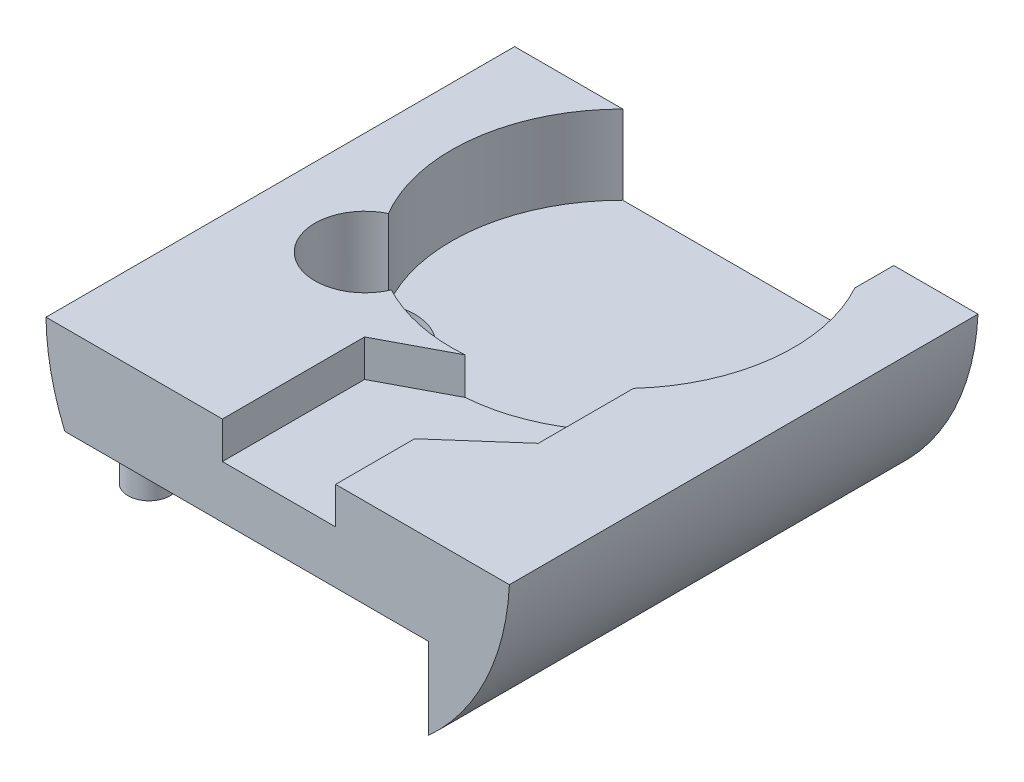
SolidWorks part; units mm, degrees
ref_plane "Front Plane" through (0, 0, 0) normal (0, 0, 1) x (1, 0, 0)
ref_plane "Top Plane" through (0, 0, 0) normal (0, 1, 0) x (1, 0, 0)
ref_plane "Right Plane" through (0, 0, 0) normal (1, 0, 0) x (0, 0, -1)
sketch "Sketch1" plane through (0, 0, 0) normal (0, 1, 0) x (1, 0, 0)
  line L0 (-43.9761, 42) -> (-43.9761, -42)
  line L1 (-43.9761, -42) -> (43.9761, -42)
  line L2 (43.9761, 42) -> (43.9761, -42)
  line L3 (-43.9761, 42) -> (43.9761, 42)
sketch "Sketch2" plane through (0, 0, 0) normal (0, 1, 0) x (1, 0, 0)
extrude "Boss-Extrude1" add sketch "Sketch1" along normal blind 44
sketch "Sketch3" plane through (0, 0, 42) normal (0, 0, 1) x (1, 0, 0)
  line L1 (-43.9761, 44) -> (43.9761, 44) construction
  line L2 (-43.9761, 0) -> (43.9761, 0) construction
  line L3 (-21, 0) -> (21, 0)
  line L5 (-43.9761, 44) -> (-43.9761, -11.9712)
  line L6 (-43.9761, -11.9712) -> (43.9761, -11.9712)
  line L7 (43.9761, -11.9712) -> (43.9761, 44)
  arc A0 (-43.9761, 44) -> (-21, 0) centre (29.2513, 54.2392) ccw
  arc A1 (21, 0) -> (43.9761, 44) centre (-19.1343, 48.9563) ccw
  point P9 (0, 0)
  dimension "D1" = 42
extrude "Cut-Extrude1" cut sketch "Sketch3" against normal through all
sketch "Sketch4" plane through (0, 0, 42) normal (0, 0, 1) x (1, 0, 0)
  line L2 (-40.0146, 44.5539) -> (-43.9761, 44)
  line L3 (-19.4066, 4) -> (19.5435, 4)
  line L4 (-19.4066, 4) -> (19.5435, 4)
  line L5 (-21, 0) -> (21, 0)
  line L6 (-21, 0) -> (21, 0) construction
  line L7 (39.9883, 44.3132) -> (43.9761, 44)
  arc A4 (-43.9761, 44) -> (-21, 0) centre (29.2513, 54.2392) ccw
  arc A5 (43.9761, 44) -> (21, 0) centre (-19.1343, 48.9563) cw
  arc A6 (19.5435, 4) -> (39.9883, 44.3132) centre (-19.1343, 48.9563) ccw
  arc A7 (-40.0146, 44.5539) -> (-19.4066, 4) centre (29.2513, 54.2392) ccw
  arc A8 (19.5435, 4) -> (39.9883, 44.3132) centre (-19.1343, 48.9563) ccw
  arc A9 (-40.0146, 44.5539) -> (-19.4066, 4) centre (29.2513, 54.2392) ccw
  dimension "D1" = 4
extrude "Cut-Extrude2" cut sketch "Sketch4" against normal blind 94
sketch "Sketch6" plane through (0, 0, -42) normal (0, 0, -1) x (-1, 0, 0)
  line L4 (-19.5435, 4) -> (19.4066, 4)
  line L5 (39.9349, 44) -> (-39.9629, 44)
  line L6 (-19.5435, 4) -> (19.4066, 4)
  line L7 (39.9349, 44) -> (-39.9629, 44)
  arc A4 (19.4066, 4) -> (39.9349, 44) centre (-29.2513, 54.2392) ccw
  arc A5 (-39.9629, 44) -> (-19.5435, 4) centre (19.1343, 48.9563) ccw
  arc A6 (19.4066, 4) -> (39.9349, 44) centre (-29.2513, 54.2392) ccw
  arc A7 (-39.9629, 44) -> (-19.5435, 4) centre (19.1343, 48.9563) ccw
  dimension "D1" = 0
extrude "Boss-Extrude2" add sketch "Sketch6" along normal blind 5
sketch "Sketch8" plane through (0, 0, -47) normal (0, 0, -1) x (-1, 0, 0)
  line L26 (-19.5435, 4) -> (19.4066, 4)
  line L27 (-21.7534, 6) -> (21.39, 6)
  arc A0 (-39.9629, 44) -> (-19.5435, 4) centre (19.1343, 48.9563) ccw construction
  arc A1 (19.4066, 4) -> (39.9349, 44) centre (-29.2513, 54.2392) ccw construction
  arc A2 (-21.7534, 6) -> (-19.5435, 4) centre (19.1343, 48.9563) ccw
  arc A3 (21.39, 6) -> (19.4066, 4) centre (-29.2513, 54.2392) cw
  dimension "D1" = 2
sketch "Sketch10" plane through (0, 0, -47) normal (0, 0, -1) x (-1, 0, 0)
extrude "Cut-Extrude4" cut sketch "Sketch8" against normal through all
sketch "Sketch11" plane through (0, 0, -47) normal (0, 0, -1) x (-1, 0, 0)
  line L0 (-21.7534, 6) -> (21.39, 6)
  line L1 (-44.6152, 44) -> (43.3848, 44)
  arc A2 (21.39, 6) -> (43.3848, 44) centre (-1.3442, 44.5242) ccw
  arc A3 (-21.7534, 6) -> (-44.6152, 44) centre (2.13, 46.246) cw
  point P7 (-0.6152, 44)
  dimension "D1" = 88
extrude "Boss-Extrude3" add sketch "Sketch11" against normal up to surface (89 mm away) up to face at (0.2349, 24.2233, 42)
sketch "Sketch12" plane through (0, 6, 0) normal (0, -1, 0) x (1, 0, 0)
  line L0 (-21.39, 42) -> (21.7534, 42) construction
  line L1 (29.2534, 42) -> (-37.39, 42)
  line L2 (29.2534, 42) -> (29.2534, -47)
  line L3 (29.2534, -47) -> (-37.39, -47)
  line L4 (-37.39, 42) -> (-37.39, -47)
  line L5 (-21.39, -47) -> (21.7534, -47) construction
  line L6 (21.7534, 42) -> (21.7534, -47) construction
  line L7 (-21.39, 42) -> (-21.39, -47) construction
  dimension "D1" = 0
  dimension "D2" = 0
  dimension "D3" = 7.5
  dimension "D4" = 16
extrude "Cut-Extrude5" cut sketch "Sketch12" against normal blind 21
sketch "Sketch13" plane through (-37.39, 0, 0) normal (1, 0, 0) x (0, 0, -1)
  line L8 (-42, 22.1497) -> (47, 22.1497)
  line L9 (47, 22.1497) -> (47, 27)
  line L10 (47, 27) -> (-42, 27)
  line L11 (-42, 27) -> (-42, 22.1497)
  line L12 (-42, 22.1497) -> (47, 22.1497)
  line L13 (47, 22.1497) -> (47, 27)
  line L14 (47, 27) -> (-42, 27)
  line L15 (-42, 27) -> (-42, 22.1497)
  dimension "D1" = 0
extrude "Cut-Extrude6" cut sketch "Sketch13" against normal blind 15
sketch "Sketch14" plane through (0, 27, 0) normal (0, -1, 0) x (1, 0, 0)
  line L0 (29.2534, 42) -> (-39.8124, 42) construction
  line L1 (-39.8124, 42) -> (-39.8124, -47) construction
  circle A0 centre (-23.8124, 1) radius 9.5
  point P6 (-71.8109, 24.8298)
  dimension "D3" = 19
  dimension "D1" = 41
  dimension "16" = 16
extrude "Cut-Extrude7" cut sketch "Sketch14" against normal through all
sketch "Sketch15" plane through (0, 27, 0) normal (0, -1, 0) x (1, 0, 0)
  line L0 (-39.8124, -47) -> (29.2534, -47) construction
  line L1 (-39.8124, 42) -> (-39.8124, -47) construction
  line L2 (29.2534, -47) -> (29.2534, 42) construction
  line L3 (29.2534, 42) -> (-39.8124, 42) construction
  circle A0 centre (-28.7124, 37.1) radius 1.5
  circle A1 centre (24.2534, -0.4) radius 1.5
  circle A2 centre (-30.8124, -34.8) radius 1.5
  circle A3 centre (-28.7124, 37.1) radius 4
  circle A4 centre (24.2534, -0.4) radius 4
  circle A5 centre (-30.8124, -34.8) radius 4
  dimension "D2" = 3
  dimension "D5" = 3
  dimension "D8" = 3
  dimension "D1" = 12.2
  dimension "D3" = 9
  dimension "46.5" = 46.6
  dimension "D4" = 5
  dimension "D6" = 11.1
  dimension "D7" = 4.9
  dimension "D9" = 2.5
extrude "Boss-Extrude4" add sketch "Sketch15" along normal blind 5.5
sketch "Sketch16" plane through (0, 44, 0) normal (0, 1, 0) x (1, 0, 0)
  line L0 (-43.3848, 47) -> (44.6152, 47) construction
  line L1 (44.6152, -42) -> (44.6152, 47) construction
  line L2 (-9.8848, -42) -> (11.6152, -42)
  line L3 (-43.3848, -42) -> (44.6152, -42) construction
  line L4 (24.1152, -16) -> (24.1152, 2.0854)
  line L5 (-9.8848, -42) -> (-9.8848, -15)
  line L6 (11.6152, -42) -> (11.6152, -27)
  line L7 (2.6152, -8.4037) -> (-9.8848, -15)
  line L8 (24.1152, -16) -> (11.6152, -27)
  line L9 (28.6152, 47) -> (28.6152, 39.6205)
  line L10 (28.6152, 47) -> (23.0771, 47)
  arc A0 (23.0771, 47) -> (2.6152, -8.4037) centre (0.1152, 24) ccw
  arc A1 (24.1152, 2.0854) -> (28.6152, 39.6205) centre (0.1152, 24) ccw
  point P4 (0.6152, 47)
  dimension "D3" = 65
  dimension "D1" = 23
  dimension "D2" = 44.5
  dimension "D4" = 16
  dimension "D7" = 21.5
  dimension "D8" = 27
  dimension "D9" = 26
  dimension "D10" = 15
extrude "Cut-Extrude8" cut sketch "Sketch16" against normal blind 7
sketch "Sketch17" plane through (0, 37, 0) normal (0, 1, 0) x (1, 0, 0)
  circle A0 centre (0.1152, 24) radius 32.5
extrude "Cut-Extrude9" cut sketch "Sketch17" against normal blind 8
equation "\"diamete\"= 50"
equation "\"hight\"= 44"
equation "\"D1@Boss-Extrude1\"=\"hight\""
equation "\"l0\"=2.04537"
equation "\"hole_diameter\"=3"
equation "\"D2@Sketch15\"=\"hole_diameter\""
equation "\"D5@Sketch15\"=\"hole_diameter\""
equation "\"D8@Sketch15\"=\"hole_diameter\""
equation "\"hole_sift\"= 5.5"
equation "\"D1@Boss-Extrude4\"=\"hole_sift\""
equation "\"tank_cut\"= 7"
equation "\"D1@Cut-Extrude8\"=\"tank_cut\""
equation "\"tank_cut_2\"=8"
equation "\"D1@Cut-Extrude9\"=\"tank_cut_2\""
